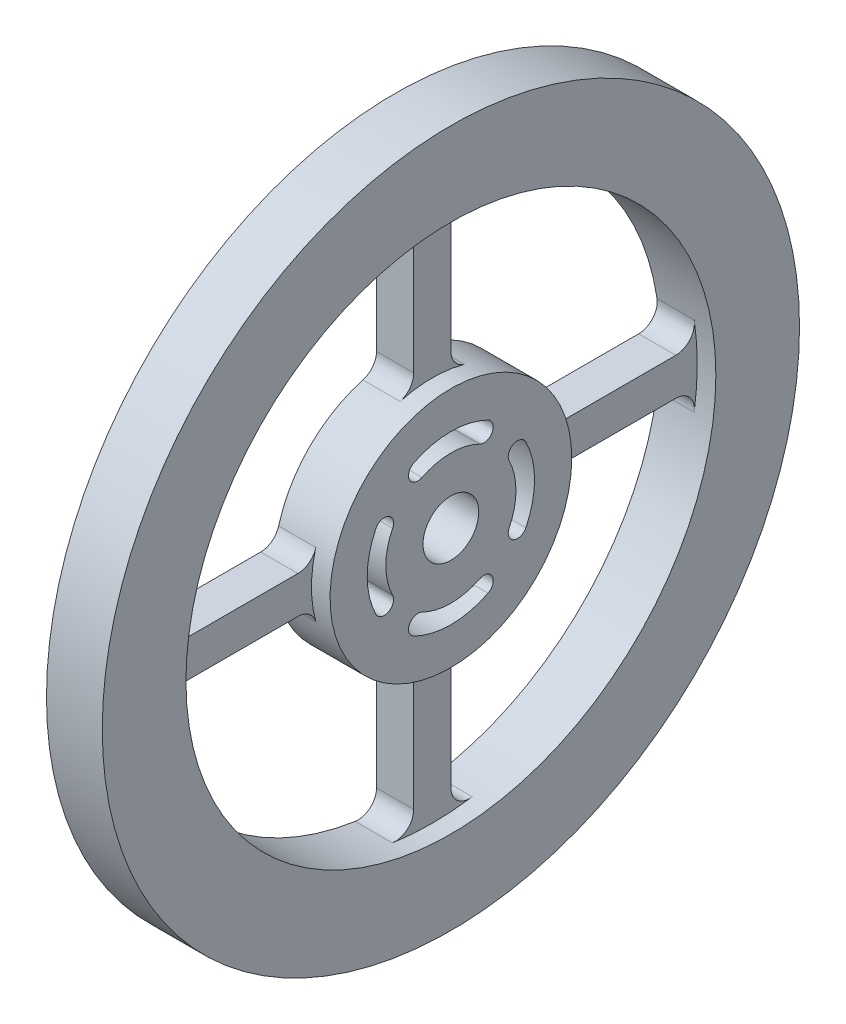
SolidWorks part; units mm, degrees
material "Acrylic (Medium-high impact)"
ref_plane "Front Plane" through (0, 0, 0) normal (0, 0, 1) x (1, 0, 0)
ref_plane "Top Plane" through (0, 0, 0) normal (0, 1, 0) x (1, 0, 0)
ref_plane "Right Plane" through (0, 0, 0) normal (1, 0, 0) x (0, 0, -1)
sketch "Sketch1" plane through (0, 0, 0) normal (1, 0, 0) x (0, 0, -1)
  line L0 (0, 0) -> (0, 37.5) construction
  line L1 (-2, 28.4297) -> (-2, 12.8452)
  line L2 (2, 28.4297) -> (2, 12.8452)
  line L3 (28.4297, 2) -> (12.8452, 2)
  line L4 (28.4297, -2) -> (12.8452, -2)
  line L5 (2, -28.4297) -> (2, -12.8452)
  line L6 (-2, -28.4297) -> (-2, -12.8452)
  line L7 (-28.4297, -2) -> (-12.8452, -2)
  line L8 (-28.4297, 2) -> (-12.8452, 2)
  circle A0 centre (0, 0) radius 37.5
  circle A2 centre (0, 0) radius 28.5
  circle A3 centre (0, 0) radius 3
  circle A4 centre (0, 0) radius 13
  point P23 (0, 0)
  point P29 (0, 0)
  dimension "D1" = 75
  dimension "D3" = 6
  dimension "D6" = 4
  dimension "D2" = 9
  dimension "D4" = 10
  dimension "D5" = 4
extrude "Boss-Extrude1" add sketch "Sketch1" along normal blind 6
fillet "Fillet1" radius 2 15 edges at (3, 12.8452, -2) (3, 28.4297, -2) (3, 28.4297, 2) (3, 12.8452, 2) (3, -2, 12.8452) (3, -2, 28.4297) (3, -28.4297, 2) (3, -28.4297, -2) (3, -12.8452, -2) (3, -2, -28.4297) (3, -2, -12.8452) (3, 2, -12.8452) (3, 2, -28.4297) (3, 2, 28.4297) (3, 2, 12.8452)
sketch "Sketch2" plane through (6, 0, 0) normal (1, 0, 0) x (0, 0, -1)
  line L0 (0, 0) -> (0, 11.7058) construction
  line L1 (3.1111, 6.2706) -> (4, 8.0623) construction
  arc A0 (0, 9) -> (4, 8.0623) centre (0, 0) cw
  arc A1 (0, 7) -> (3.1111, 6.2706) centre (0, 0) cw
  circle A2 centre (3.5556, 7.1665) radius 1
  circle A3 centre (-3.5556, 7.1665) radius 1
  arc A4 (0, 7) -> (-3.1111, 6.2706) centre (0, 0) ccw
  arc A5 (0, 9) -> (-4, 8.0623) centre (0, 0) ccw
  dimension "D1" = 9
  dimension "D2" = 4
  dimension "D3" = 2
extrude "Cut-Extrude1" cut sketch "Sketch2" against normal blind 10 contours A0 A5 A3 A4 A1 A2 | A3 | A2
pattern_circular "CirPattern1" count 4 over 360 about axis through (0, 0, 0) along (1, 0, 0) of "Cut-Extrude1"
sketch "Sketch3" plane through (6, 0, 0) normal (1, 0, 0) x (0, 0, -1)
  circle A0 centre (0, 0) radius 13
  circle A1 centre (0, 0) radius 28.5
extrude "Cut-Extrude2" cut sketch "Sketch3" against normal blind 2
